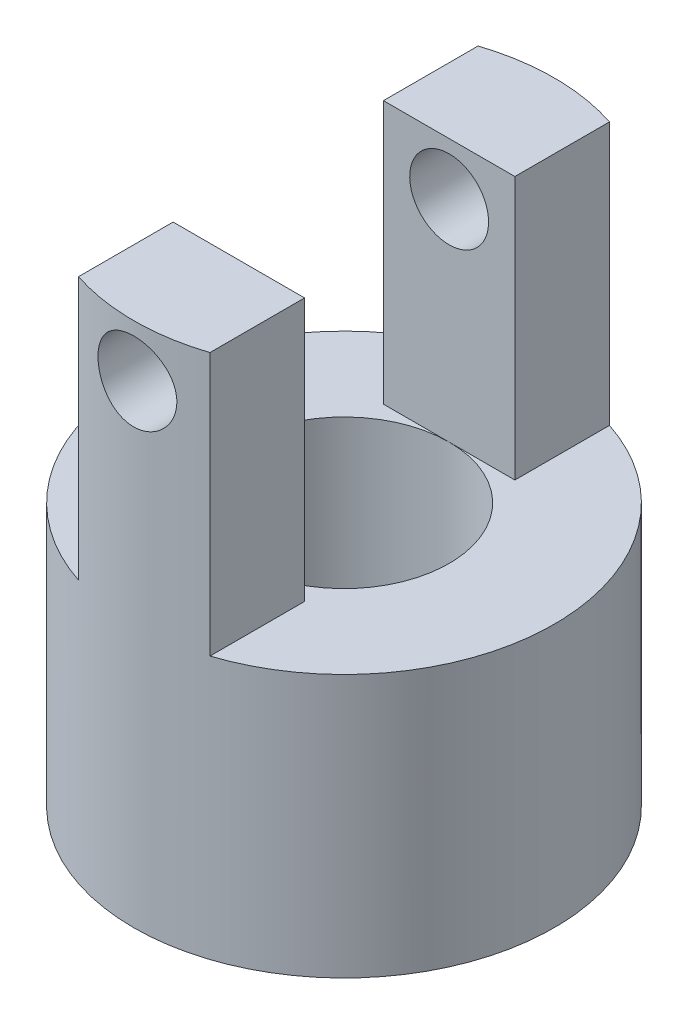
SolidWorks part; units mm, degrees
ref_plane "前视基准面" through (0, 0, 0) normal (0, 0, 1) x (1, 0, 0)
ref_plane "上视基准面" through (0, 0, 0) normal (0, 1, 0) x (1, 0, 0)
ref_plane "右视基准面" through (0, 0, 0) normal (1, 0, 0) x (0, 0, -1)
other "Configuration Table"
sketch "草图1" plane through (0, 0, 0) normal (0, 1, 0) x (1, 0, 0)
  circle A0 centre (0, 0) radius 8
  dimension "D1" = 16
extrude "凸台-拉伸1" add sketch "草图1" along normal blind 20
sketch "草图2" plane through (0, 0, 0) normal (0, 0, 1) x (1, 0, 0)
  line L1 (-8, 20) -> (-2.5, 20)
  line L2 (-8, 20) -> (-8, 10)
  line L3 (-8, 10) -> (-2.5, 10)
  line L4 (-2.5, 20) -> (-2.5, 10)
  line L5 (8, 20) -> (2.5, 20)
  line L6 (8, 20) -> (8, 10)
  line L7 (8, 10) -> (2.5, 10)
  line L8 (2.5, 20) -> (2.5, 10)
  dimension "D1" = 5
  dimension "D2" = 10
extrude "切除-拉伸1" cut sketch "草图2" against normal through all both and the other way through all
sketch "草图3" plane through (-2.5, 0, 0) normal (-1, 0, 0) x (0, 0, 1)
  line L0 (7.5993, 20) -> (-7.5993, 20) construction
  line L1 (-4, 20) -> (4, 20)
  line L2 (-4, 20) -> (-4, 10)
  line L3 (-4, 10) -> (4, 10)
  line L4 (4, 20) -> (4, 10)
  line L5 (-7.5993, 10) -> (7.5993, 10) construction
  point P8 (0, 20)
  dimension "D1" = 8
extrude "切除-拉伸2" cut sketch "草图3" against normal through all both
sketch "草图4" plane through (0, 0, 0) normal (0, 0, 1) x (1, 0, 0)
  line L0 (0, 20) -> (0, 10) construction
  circle A0 centre (0, 18) radius 1.5
  dimension "D1" = 3
  dimension "D2" = 18
extrude "切除-拉伸3" cut sketch "草图4" against normal through all both and the other way through all
sketch "草图5" plane through (0, 0, 0) normal (0, -1, 0) x (1, 0, 0)
  circle A0 centre (0, 0) radius 4
  dimension "D1" = 8
extrude "切除-拉伸4" cut sketch "草图5" against normal through all both
